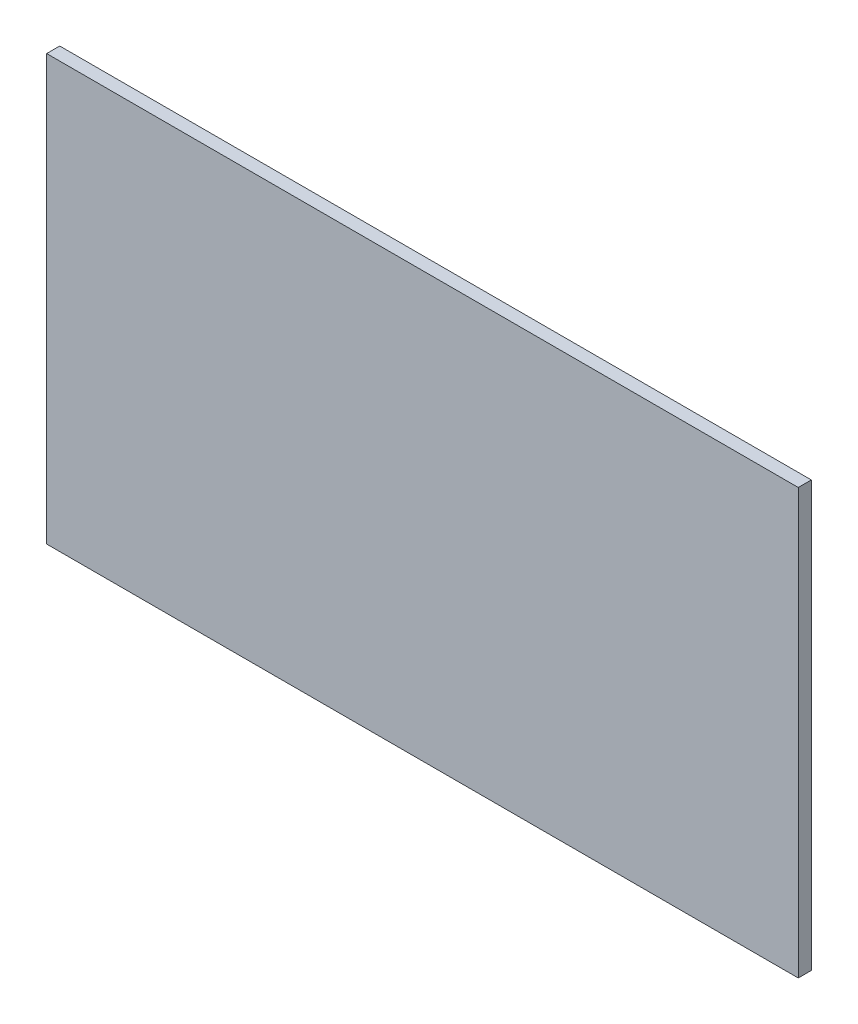
SolidWorks part; units mm, degrees
ref_plane "Alzado" through (0, 0, 0) normal (0, 0, 1) x (1, 0, 0)
ref_plane "Planta" through (0, 0, 0) normal (0, 1, 0) x (1, 0, 0)
ref_plane "Vista lateral" through (0, 0, 0) normal (1, 0, 0) x (0, 0, -1)
sketch "Croquis1" plane through (0, 0, 0) normal (0, 0, 1) x (1, 0, 0)
  line L1 (0, 0) -> (230, 0)
  line L2 (0, 0) -> (0, -130)
  line L3 (0, -130) -> (230, -130)
  line L4 (230, 0) -> (230, -130)
  dimension "D1" = 230
  dimension "D2" = 130
extrude "Saliente-Extruir1" add sketch "Croquis1" along normal blind 4
